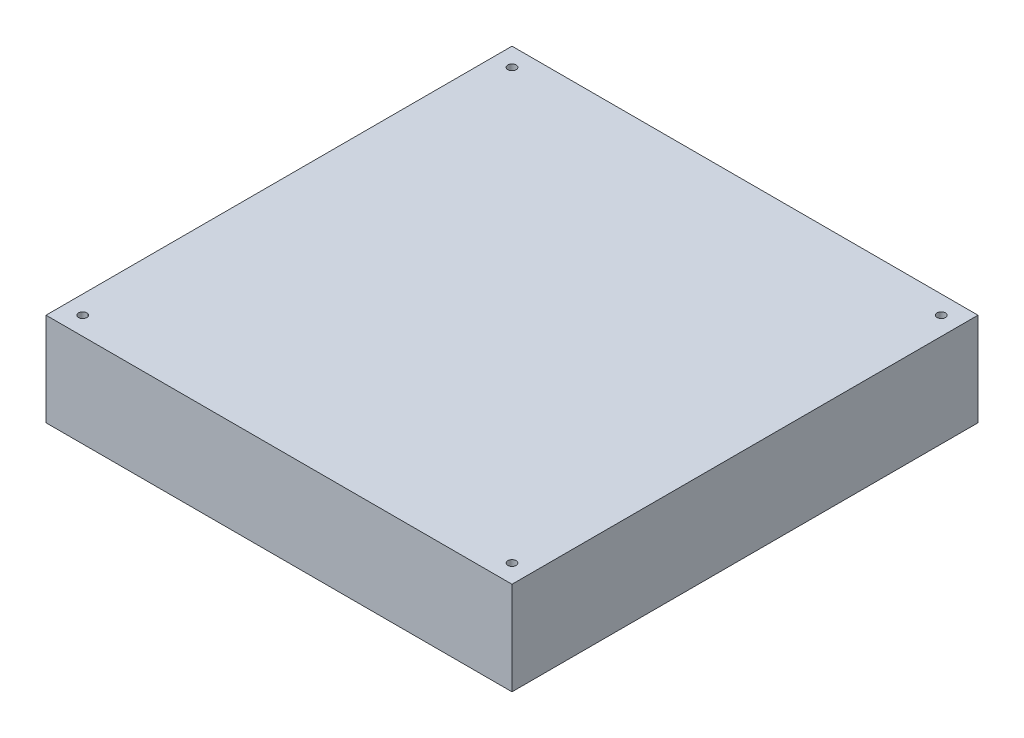
SolidWorks part; units mm, degrees
ref_plane "Front Plane" through (0, 0, 0) normal (0, 0, 1) x (1, 0, 0)
ref_plane "Top Plane" through (0, 0, 0) normal (0, 1, 0) x (1, 0, 0)
ref_plane "Right Plane" through (0, 0, 0) normal (1, 0, 0) x (0, 0, -1)
sketch "Sketch1" plane through (0, 0, 0) normal (0, 1, 0) x (1, 0, 0)
  line L1 (-63.5, 63.5) -> (63.5, 63.5)
  line L2 (-63.5, 63.5) -> (-63.5, -63.5)
  line L3 (-63.5, -63.5) -> (63.5, -63.5)
  line L4 (63.5, 63.5) -> (63.5, -63.5)
  line L5 (-63.5, 63.5) -> (63.5, -63.5) construction
  line L6 (-63.5, -63.5) -> (63.5, 63.5) construction
  point P0 (0, 0)
  dimension "D1" = 127
  dimension "D2" = 127
extrude "Boss-Extrude1" add sketch "Sketch1" along normal blind 25.4
sketch "Sketch4" plane through (0, 25.4, 0) normal (0, 1, 0) x (1, 0, 0)
  line L0 (0, 0) -> (0, -63.5) construction
  line L1 (-63.5, -63.5) -> (63.5, -63.5) construction
  line L3 (0, 0) -> (-63.5, 0) construction
  line L4 (-63.5, 63.5) -> (-63.5, -63.5) construction
  circle A0 centre (-58.5, -58.5) radius 1.1303
  circle A1 centre (58.5, -58.5) radius 1.1303
  circle A2 centre (58.5, 58.5) radius 1.1303
  circle A3 centre (-58.5, 58.5) radius 1.1303
  dimension "0.089" = 2.2606
  dimension "D2" = 58.5
  dimension "D3" = 58.5
extrude "Cut-Extrude1" cut sketch "Sketch4" against normal up to surface (25.4 mm away) up to face at (0, 0, 0)
